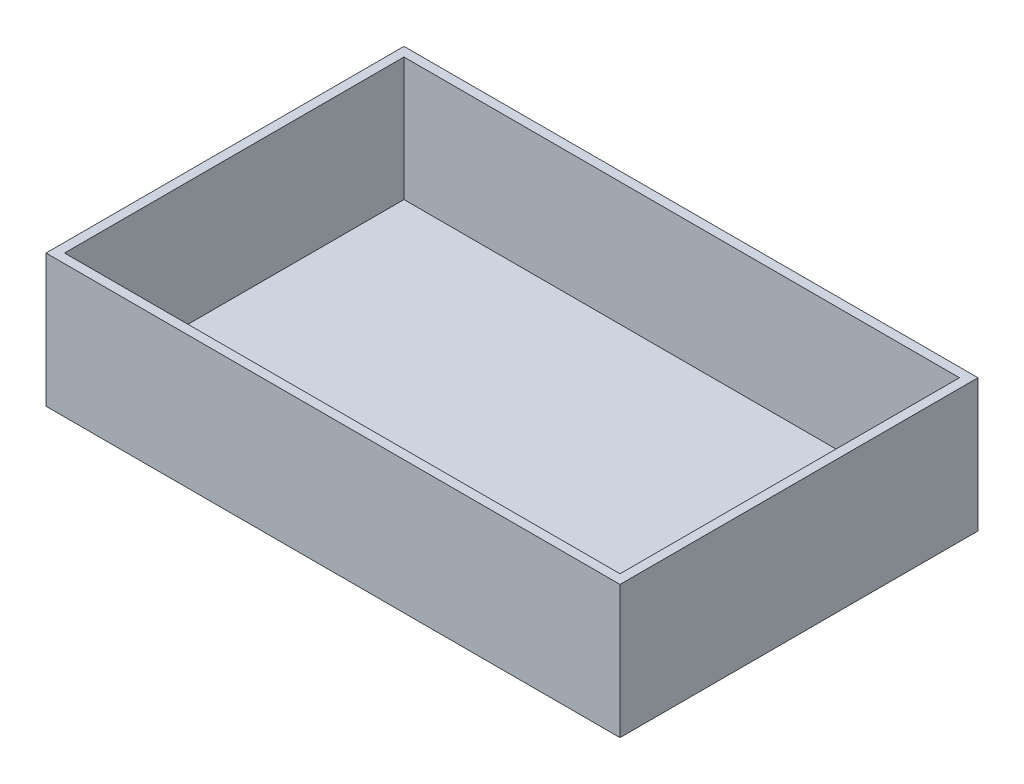
SolidWorks part; units mm, degrees
ref_plane "Plano frontal" through (0, 0, 0) normal (0, 0, 1) x (1, 0, 0)
ref_plane "Plano superior" through (0, 0, 0) normal (0, 1, 0) x (1, 0, 0)
ref_plane "Plano direito" through (0, 0, 0) normal (1, 0, 0) x (0, 0, -1)
sketch "Esboço1" plane through (0, 0, 0) normal (0, 1, 0) x (1, 0, 0)
  line L0 (-89.8905, 62.8051) -> (0.1095, 62.8051)
  line L5 (-89.8905, 62.8051) -> (-89.8905, 7.8051)
  line L6 (-89.8905, 7.8051) -> (0.1095, 7.8051)
  line L7 (0.1095, 62.8051) -> (0.1095, 7.8051)
extrude "Ressalto-extrusão1" add sketch "Esboço1" along normal blind 20 contours L0 L7 L6 L5
sketch "Esboço2" plane through (0, 20, 0) normal (0, 1, 0) x (1, 0, 0)
shell "Casca1" thickness 1.5
